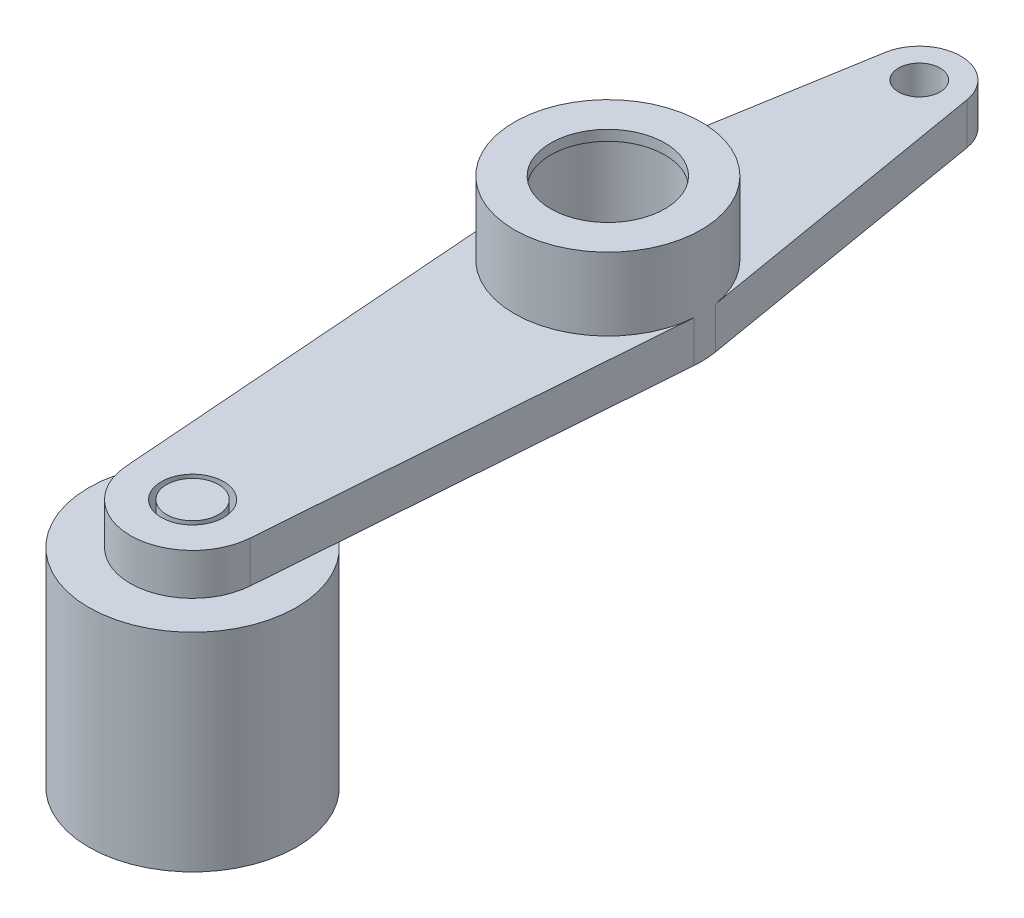
SolidWorks part; units mm, degrees
ref_plane "前视基准面" through (0, 0, 0) normal (0, 0, 1) x (1, 0, 0)
ref_plane "上视基准面" through (0, 0, 0) normal (0, 1, 0) x (1, 0, 0)
ref_plane "右视基准面" through (0, 0, 0) normal (1, 0, 0) x (0, 0, -1)
sketch "草图1" plane through (0, 0, 0) normal (0, 1, 0) x (1, 0, 0)
  line L0 (0, 0) -> (0, -40) construction
  line L1 (0, 0) -> (0, 30) construction
  line L3 (-8.9747, -0.675) -> (-5.9831, -40.45)
  line L4 (8.9747, -0.675) -> (5.9831, -40.45)
  line L5 (-8.8741, 1.5) -> (-3.9441, 30.6667)
  line L7 (3.9441, 30.6667) -> (8.8741, 1.5)
  arc A0 (3.9441, 30.6667) -> (-3.9441, 30.6667) centre (0, 30) ccw
  arc A1 (-8.8741, 1.5) -> (-8.9747, -0.675) centre (0, 0) ccw
  arc A2 (-5.9831, -40.45) -> (5.9831, -40.45) centre (0, -40) ccw
  arc A4 (8.9747, -0.675) -> (8.8741, 1.5) centre (0, 0) ccw
  dimension "D1" = 30
  dimension "D2" = 9
  dimension "D6" = 12
  dimension "D8" = 8
  dimension "D3" = 180
  dimension "D4" = 40
extrude "凸台-拉伸1" add sketch "草图1" along normal blind 4
sketch "草图3" plane through (0, 4, 0) normal (0, 1, 0) x (1, 0, 0)
  circle A0 centre (0, 0) radius 9
extrude "凸台-拉伸2" add sketch "草图3" along normal blind 7
sketch "草图4" plane through (0, 4, 0) normal (0, 1, 0) x (1, 0, 0)
  circle A0 centre (0, -40) radius 3
  dimension "D1" = 6
extrude "切除-拉伸1" cut sketch "草图4" against normal through all
sketch "草图5" plane through (0, 0, 0) normal (0, -1, 0) x (1, 0, 0)
  circle A0 centre (0, 0) radius 6
  dimension "D1" = 12
extrude "切除-拉伸2" cut sketch "草图5" against normal blind 10
sketch "草图7" plane through (0, 11, 0) normal (0, 1, 0) x (1, 0, 0)
  circle A0 centre (0, 0) radius 5.5
  dimension "D1" = 11
extrude "切除-拉伸3" cut sketch "草图7" against normal through all
hole_wizard "Ø4.0 (4) 直径孔1" positions "草图9" profile "草图10" hole size "Ø4.0" standard "GB" end condition through all
sketch "草图9" plane through (0, 4, 0) normal (0, 1, 0) x (1, 0, 0)
  point P0 (0, 30)
sketch "草图10" plane through (0, 4, -30) normal (1, 0, 0) x (0, 0, 1)
  line L0 (0, 0) -> (0, 4)
  line L1 (0, 4) -> (2, 4)
  line L2 (2, 4) -> (2, 0)
  line L5 (2, 0) -> (0, 0)
  line L11 (0, -6.35) -> (0, 107.95) construction
  dimension "通孔孔直径" = 4
  dimension "通孔孔深度" = 4
scale "Scale1" scale about centroid uniform scaling yes scale factor 2
sketch "Sketch1" plane through (0, -3.1889, 0) normal (0, -1, 0) x (1, 0, 0)
  circle A0 centre (0, 74.1246) radius 20
  dimension "D1" = 40
extrude "Extrude1" add sketch "Sketch1" along normal blind 40
sketch "Sketch2" plane through (0, -3.1889, 0) normal (0, 1, 0) x (1, 0, 0)
  circle A0 centre (0, -74.1246) radius 5
  dimension "D1" = 10
extrude "Extrude2" add sketch "Sketch2" along normal blind 8
sketch "Sketch3" plane through (0, -43.1889, 0) normal (0, -1, 0) x (1, 0, 0)
  line L0 (0, 74.1246) -> (20.5002, 74.1246) construction
  line L1 (-2, 88.1246) -> (2, 88.1246)
  line L2 (-2, 88.1246) -> (-2, 87.1246)
  line L3 (-2, 87.1246) -> (2, 87.1246)
  line L4 (2, 88.1246) -> (2, 87.1246)
  line L5 (-2.4725, 61.1246) -> (2.4725, 61.1246)
  line L6 (-2.4725, 61.1246) -> (-2.4725, 60.3506)
  line L7 (-2.4725, 60.3506) -> (2.4725, 60.3506)
  line L8 (2.4725, 61.1246) -> (2.4725, 60.3506)
  point P11 (0, 87.1246)
  point P12 (0, 61.1246)
  dimension "D1" = 13
  dimension "D2" = 4
  dimension "D3" = 1
extrude "Extrude3" add sketch "Sketch3" along normal blind 4
